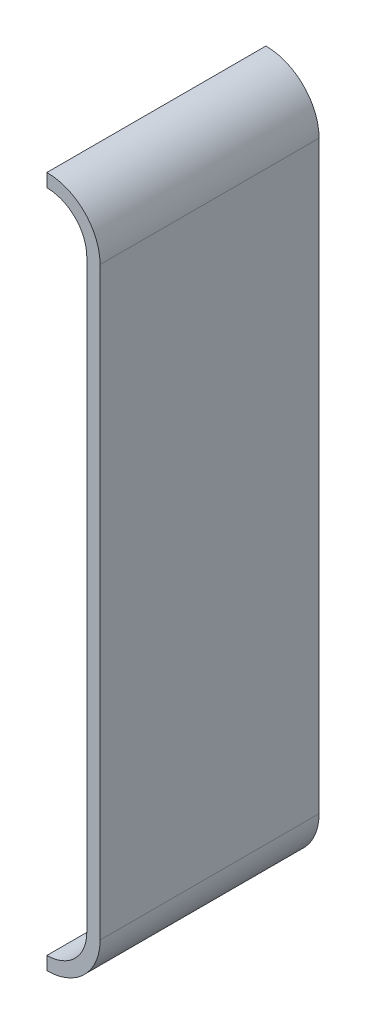
SolidWorks part; units mm, degrees
material "ABS"
ref_plane "X-Y Datum" through (0, 0, 0) normal (0, 0, 1) x (1, 0, 0)
ref_plane "X-Z Datum" through (0, 0, 0) normal (0, 1, 0) x (1, 0, 0)
ref_plane "Y-Z Datum" through (0, 0, 0) normal (1, 0, 0) x (0, 0, -1)
sketch "Sketch1" plane through (0, 0, 0) normal (1, 0, 0) x (0, 0, -1)
  line L1 (0, 0) -> (52.3, 0)
  line L2 (0, 0) -> (0, 139.7)
  line L3 (0, 139.7) -> (52.3, 139.7)
  line L4 (52.3, 0) -> (52.3, 139.7)
extrude "Boss-Extrude1" add sketch "Sketch1" along normal blind 3.175
sketch "Sketch2" plane through (0, 0, -52.3) normal (0, 0, -1) x (-1, 0, 0)
  line L0 (9.525, -9.525) -> (9.525, -12.7)
  line L1 (0, 0) -> (-3.175, 0)
  line L2 (-3.175, 69.85) -> (6.8734, 69.85) construction
  line L3 (-3.175, 0) -> (-3.175, 139.7) construction
  line L4 (0, 139.7) -> (-3.175, 139.7)
  line L5 (9.525, 149.225) -> (9.525, 152.4)
  arc A1 (-3.175, 0) -> (9.525, -12.7) centre (9.525, 0) ccw
  arc A2 (0, 0) -> (9.525, -9.525) centre (9.525, 0) ccw
  circle A3 centre (9.525, 0) radius 12.7 construction
  circle A4 centre (9.525, 0) radius 9.525 construction
  arc A5 (0, 139.7) -> (9.525, 149.225) centre (9.525, 139.7) cw
  arc A6 (-3.175, 139.7) -> (9.525, 152.4) centre (9.525, 139.7) cw
  dimension "D1" = 3.175
extrude "Boss-Extrude2" add sketch "Sketch2" against normal up to surface (52.3 mm away) up to face at (1.5875, 69.85, 0)
